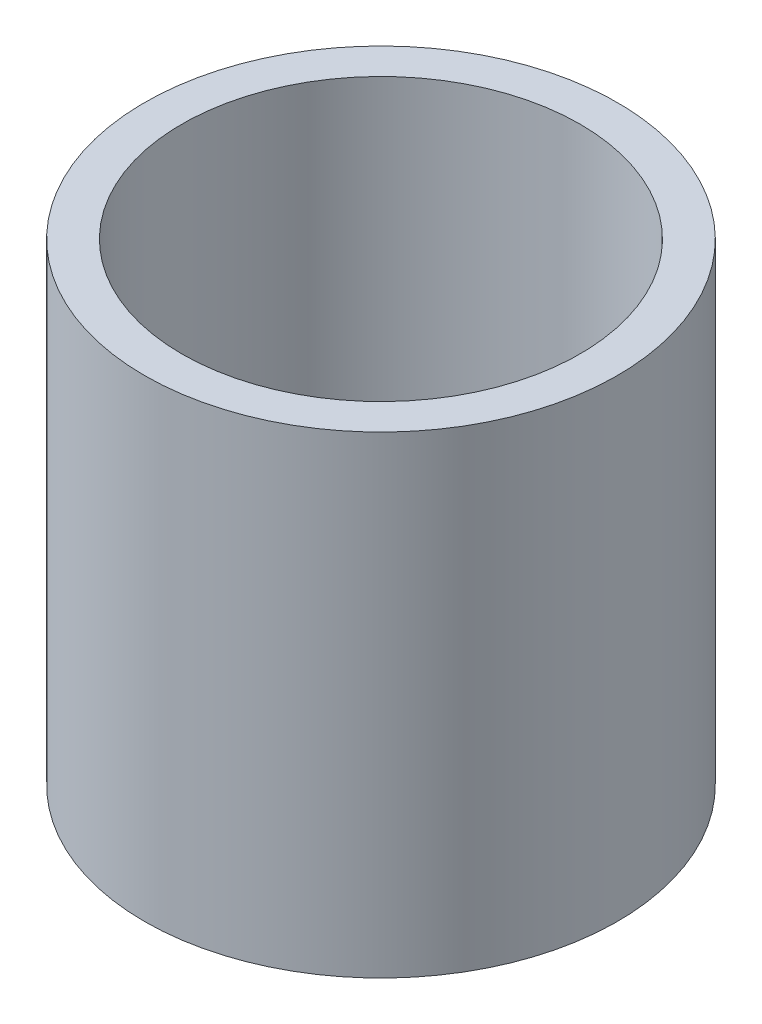
SolidWorks part; units mm, degrees
ref_plane "前视基准面" through (0, 0, 0) normal (0, 0, 1) x (1, 0, 0)
ref_plane "上视基准面" through (0, 0, 0) normal (0, 1, 0) x (1, 0, 0)
ref_plane "右视基准面" through (0, 0, 0) normal (1, 0, 0) x (0, 0, -1)
sketch "草图1" plane through (0, 0, 0) normal (0, 1, 0) x (1, 0, 0)
  circle A0 centre (0, 0) radius 9.5
  circle A1 centre (0, 0) radius 8
  dimension "D1" = 19
  dimension "D2" = 16
extrude "凸台-拉伸1" add sketch "草图1" along normal blind 19
